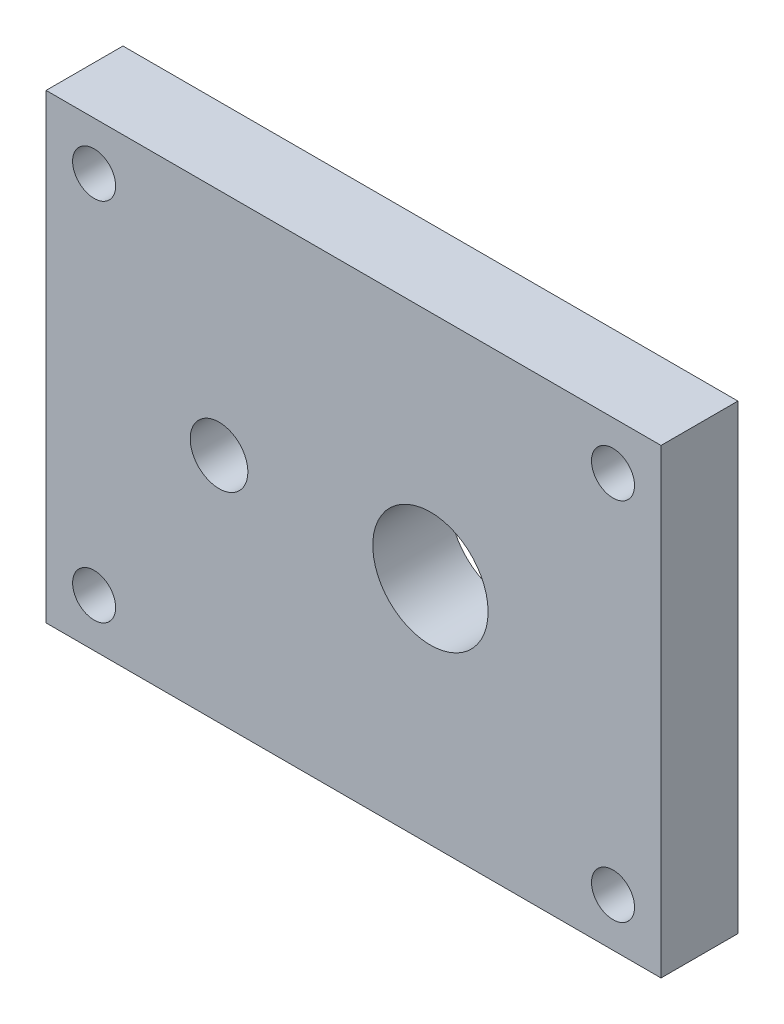
SolidWorks part; units mm, degrees
ref_plane "Front Plane" through (0, 0, 0) normal (0, 0, 1) x (1, 0, 0)
ref_plane "Top Plane" through (0, 0, 0) normal (0, 1, 0) x (1, 0, 0)
ref_plane "Right Plane" through (0, 0, 0) normal (1, 0, 0) x (0, 0, -1)
sketch "Sketch1" plane through (0, 0, 0) normal (0, 0, 1) x (1, 0, 0)
  line L0 (19.05, -19.05) -> (-31.75, -19.05) construction
  line L1 (19.05, 19.05) -> (19.05, -19.05) construction
  line L2 (-31.75, -19.05) -> (-31.75, 19.05) construction
  line L3 (-31.75, 19.05) -> (19.05, 19.05) construction
  line L4 (19.05, -19.05) -> (-31.75, -19.05)
  line L5 (19.05, 19.05) -> (19.05, -19.05)
  line L6 (-31.75, -19.05) -> (-31.75, 19.05)
  line L7 (-31.75, 19.05) -> (19.05, 19.05)
extrude "Boss-Extrude1" add sketch "Sketch1" along normal blind 6.35
sketch "Sketch2" plane through (0, 0, 6.35) normal (0, 0, 1) x (1, 0, 0)
  circle A0 centre (-17.4623, 0.083) radius 2.3813
  circle A1 centre (0, 0) radius 4.7625
  dimension "D1" = 4.7625
  dimension "D2" = 9.525
extrude "Cut-Extrude1" cut sketch "Sketch2" against normal through all
sketch "Sketch3" plane through (0, 0, 6.35) normal (0, 0, 1) x (1, 0, 0)
  line L0 (-31.75, 19.05) -> (-31.75, -19.05) construction
  line L1 (-31.75, -19.05) -> (19.05, -19.05) construction
  line L2 (19.05, -19.05) -> (19.05, 19.05) construction
  line L3 (19.05, 19.05) -> (-31.75, 19.05) construction
  circle A0 centre (-27.7813, 15.0813) radius 1.778
  circle A1 centre (15.0813, 15.0813) radius 1.778
  circle A2 centre (15.0813, -15.0813) radius 1.778
  circle A3 centre (-27.7812, -15.0813) radius 1.778
  dimension "D1" = 3.556
  dimension "D2" = 3.556
  dimension "D3" = 3.556
  dimension "D4" = 3.556
  dimension "D5" = 3.9688
  dimension "D6" = 3.9688
  dimension "D7" = 3.9688
  dimension "D8" = 3.9688
  dimension "D9" = 3.9688
  dimension "D10" = 3.9688
  dimension "D11" = 3.9688
  dimension "D12" = 3.9687
extrude "Cut-Extrude2" cut sketch "Sketch3" against normal through all
